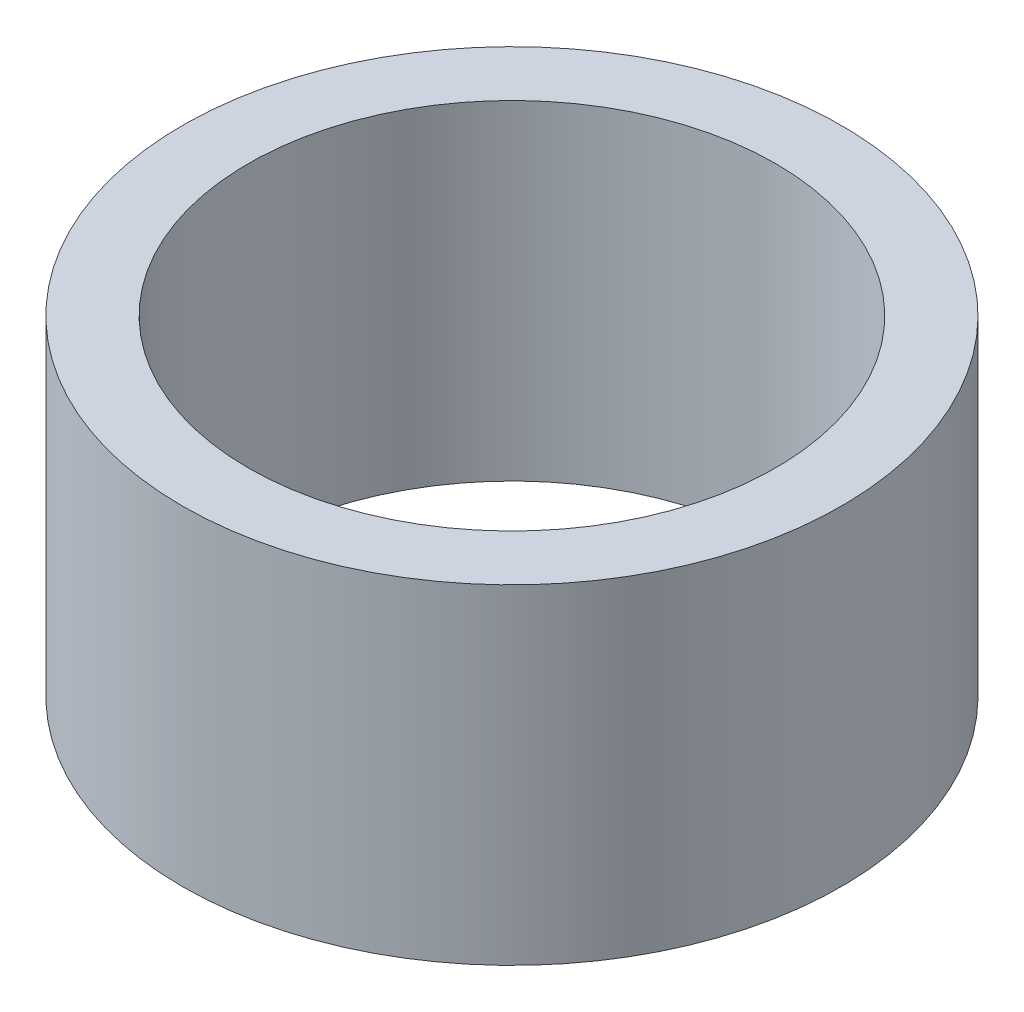
SolidWorks part; units mm, degrees
ref_plane "Front Plane" through (0, 0, 0) normal (0, 0, 1) x (1, 0, 0)
ref_plane "Top Plane" through (0, 0, 0) normal (0, 1, 0) x (1, 0, 0)
ref_plane "Right Plane" through (0, 0, 0) normal (1, 0, 0) x (0, 0, -1)
sketch "Sketch2" plane through (0, 0, 0) normal (0, 1, 0) x (1, 0, 0)
  circle A0 centre (0, 0) radius 5
  circle A1 centre (0, 0) radius 4
  dimension "D1" = 10
  dimension "D2" = 8
extrude "Boss-Extrude1" add sketch "Sketch2" along normal blind 5
